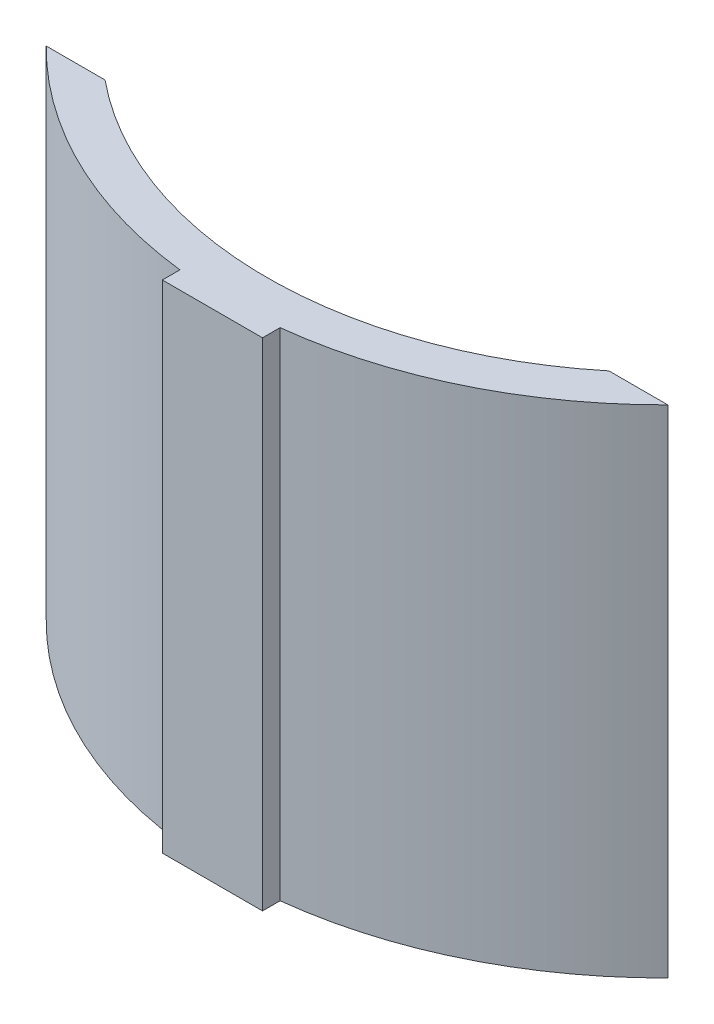
SolidWorks part; units mm, degrees
ref_plane "Front Plane" through (0, 0, 0) normal (0, 0, 1) x (1, 0, 0)
ref_plane "Top Plane" through (0, 0, 0) normal (0, 1, 0) x (1, 0, 0)
ref_plane "Right Plane" through (0, 0, 0) normal (1, 0, 0) x (0, 0, -1)
sketch "Sketch1" plane through (0, 0, 0) normal (0, 1, 0) x (1, 0, 0)
  line L0 (-15.6531, -15.459) -> (-12.6894, -15.459)
  line L2 (12.6894, -15.459) -> (15.6531, -15.459)
  line L7 (-2.5226, -22.7401) -> (2.5226, -22.7401)
  line L8 (2.5226, -21.8549) -> (2.5226, -22.7401)
  line L11 (-2.5226, -21.8549) -> (-2.5226, -22.7401)
  arc A0 (-12.6894, -15.459) -> (12.6894, -15.459) centre (0, 0) ccw
  arc A1 (2.5226, -21.8549) -> (15.6531, -15.459) centre (0, 0) ccw
  arc A2 (-15.6531, -15.459) -> (-2.5226, -21.8549) centre (0, 0) ccw
  point P4 (0, -21.1508)
  dimension "D1" = 20
extrude "Boss-Extrude1" add sketch "Sketch1" along normal blind 25
